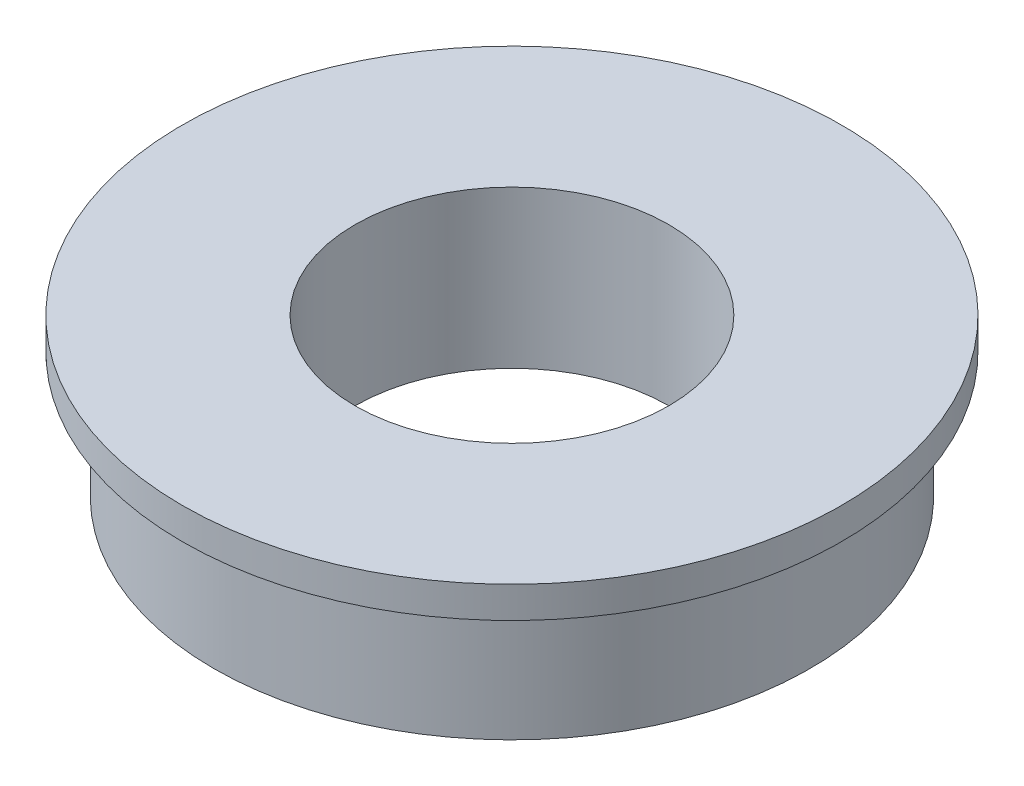
SolidWorks part; units mm, degrees
ref_plane "前视基准面" through (0, 0, 0) normal (0, 0, 1) x (1, 0, 0)
ref_plane "上视基准面" through (0, 0, 0) normal (0, 1, 0) x (1, 0, 0)
ref_plane "右视基准面" through (0, 0, 0) normal (1, 0, 0) x (0, 0, -1)
other "Configuration Table"
sketch "草图1" plane through (0, 0, 0) normal (0, 1, 0) x (1, 0, 0)
  circle A0 centre (0, 0) radius 5
  circle A1 centre (0, 0) radius 9.5
  dimension "D1" = 10
  dimension "D2" = 4.5
extrude "凸台-拉伸1" add sketch "草图1" along normal blind 5
sketch "草图2" plane through (0, 5, 0) normal (0, 1, 0) x (1, 0, 0)
  circle A0 centre (0, 0) radius 9.5
  circle A1 centre (0, 0) radius 10.5
  dimension "D1" = 19
  dimension "D2" = 1
extrude "凸台-拉伸2" add sketch "草图2" against normal blind 1
